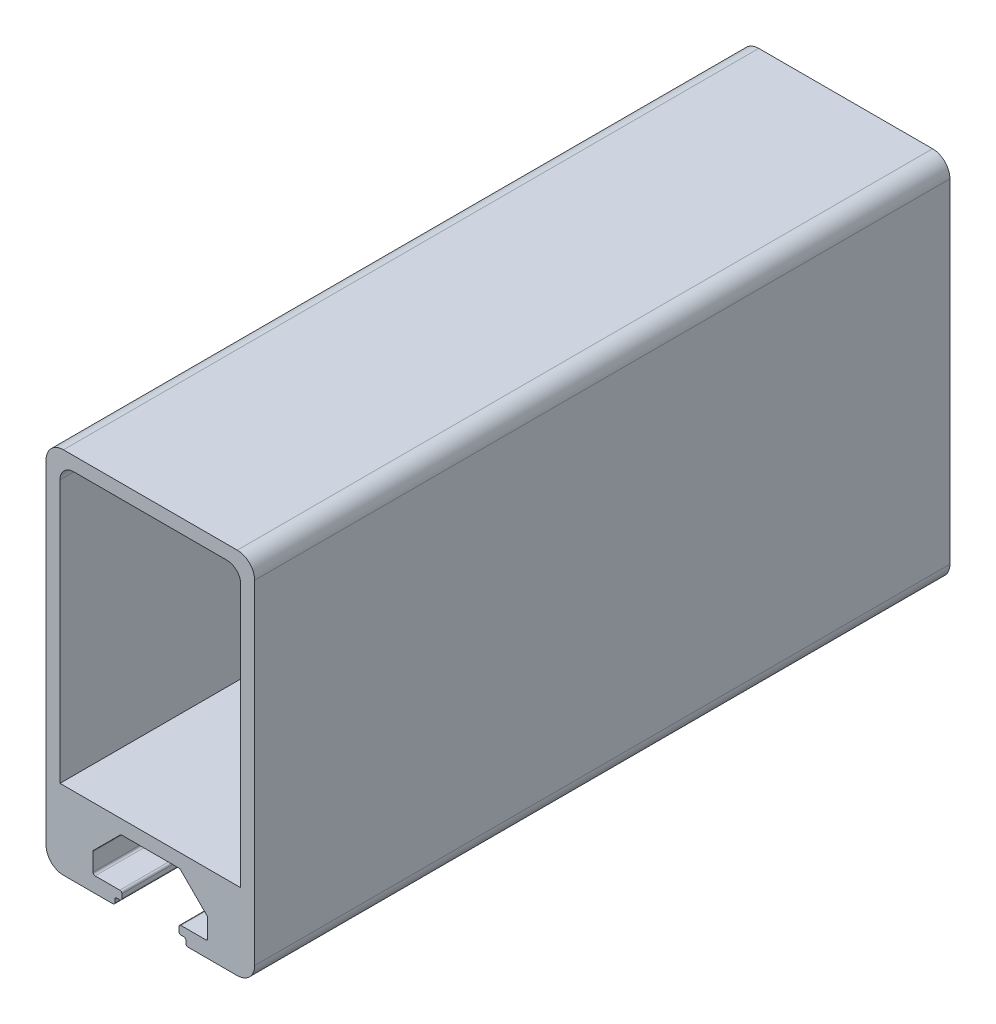
SolidWorks part; units mm, degrees
ref_plane "前视基准面" through (0, 0, 0) normal (0, 0, 1) x (1, 0, 0)
ref_plane "上视基准面" through (0, 0, 0) normal (0, 1, 0) x (1, 0, 0)
ref_plane "右视基准面" through (0, 0, 0) normal (1, 0, 0) x (0, 0, -1)
sketch "草图1" plane through (0, 0, 0) normal (0, 0, 1) x (1, 0, 0)
  line B0 (12.5, 0) -> (-12.5, 0)
  line B1 (11, -2) -> (-11, -2)
  line B2 (-15, -2.5) -> (-15, -50.5)
  line B3 (-13, -4) -> (-13, -41.8)
  line B4 (15, -2.5) -> (15, -50.5)
  line B5 (13, -4) -> (13, -41.8)
  line B6 (-5.4, -53) -> (-12.5, -53)
  line B7 (5.4, -53) -> (12.5, -53)
  line B8 (-5.1, -52.3) -> (-5.1, -52.7)
  line B9 (5.1, -52.3) -> (5.1, -52.7)
  line B10 (-4.8, -52) -> (-4.4, -52)
  line B11 (4.8, -52) -> (4.4, -52)
  line B12 (-4.1, -51.1) -> (-4.1, -51.7)
  line B13 (4.1, -51.1) -> (4.1, -51.7)
  line B14 (-7.95, -50.8) -> (-4.4, -50.8)
  line B15 (7.95, -50.8) -> (4.4, -50.8)
  line B16 (-8.25, -47.9299) -> (-8.25, -50.5)
  line B17 (8.25, -47.9299) -> (8.25, -50.5)
  line B18 (-4.3322, -43.8879) -> (-8.1621, -47.7178)
  line B19 (8.1621, -47.7178) -> (4.3322, -43.8879)
  line B20 (-4.1201, -43.8) -> (4.1201, -43.8)
  line B21 (13, -41.8) -> (-13, -41.8)
  arc B22 (-11, -2) -> (-13, -4) centre (-11, -4) ccw
  arc B23 (-12.5, 0) -> (-15, -2.5) centre (-12.5, -2.5) ccw
  arc B24 (15, -2.5) -> (12.5, 0) centre (12.5, -2.5) ccw
  arc B25 (13, -4) -> (11, -2) centre (11, -4) ccw
  arc B26 (-15, -50.5) -> (-12.5, -53) centre (-12.5, -50.5) ccw
  arc B27 (12.5, -53) -> (15, -50.5) centre (12.5, -50.5) ccw
  arc B28 (-5.4, -53) -> (-5.1, -52.7) centre (-5.4, -52.7) ccw
  arc B29 (5.1, -52.7) -> (5.4, -53) centre (5.4, -52.7) ccw
  arc B30 (-4.8, -52) -> (-5.1, -52.3) centre (-4.8, -52.3) ccw
  arc B31 (5.1, -52.3) -> (4.8, -52) centre (4.8, -52.3) ccw
  arc B32 (-4.4, -52) -> (-4.1, -51.7) centre (-4.4, -51.7) ccw
  arc B33 (4.1, -51.7) -> (4.4, -52) centre (4.4, -51.7) ccw
  arc B34 (-4.1, -51.1) -> (-4.4, -50.8) centre (-4.4, -51.1) ccw
  arc B35 (4.4, -50.8) -> (4.1, -51.1) centre (4.4, -51.1) ccw
  arc B36 (-8.25, -50.5) -> (-7.95, -50.8) centre (-7.95, -50.5) ccw
  arc B37 (7.95, -50.8) -> (8.25, -50.5) centre (7.95, -50.5) ccw
  arc B38 (-8.1621, -47.7178) -> (-8.25, -47.9299) centre (-7.95, -47.9299) ccw
  arc B39 (8.25, -47.9299) -> (8.1621, -47.7178) centre (7.95, -47.9299) ccw
  arc B40 (-4.1201, -43.8) -> (-4.3322, -43.8879) centre (-4.1201, -44.1) ccw
  arc B41 (4.3322, -43.8879) -> (4.1201, -43.8) centre (4.1201, -44.1) ccw
sketch_block_instance "A$C02824880-1"
sketch_block "A$C02824880"
extrude "凸台-拉伸1" add sketch "草图1" along normal mid plane 100
